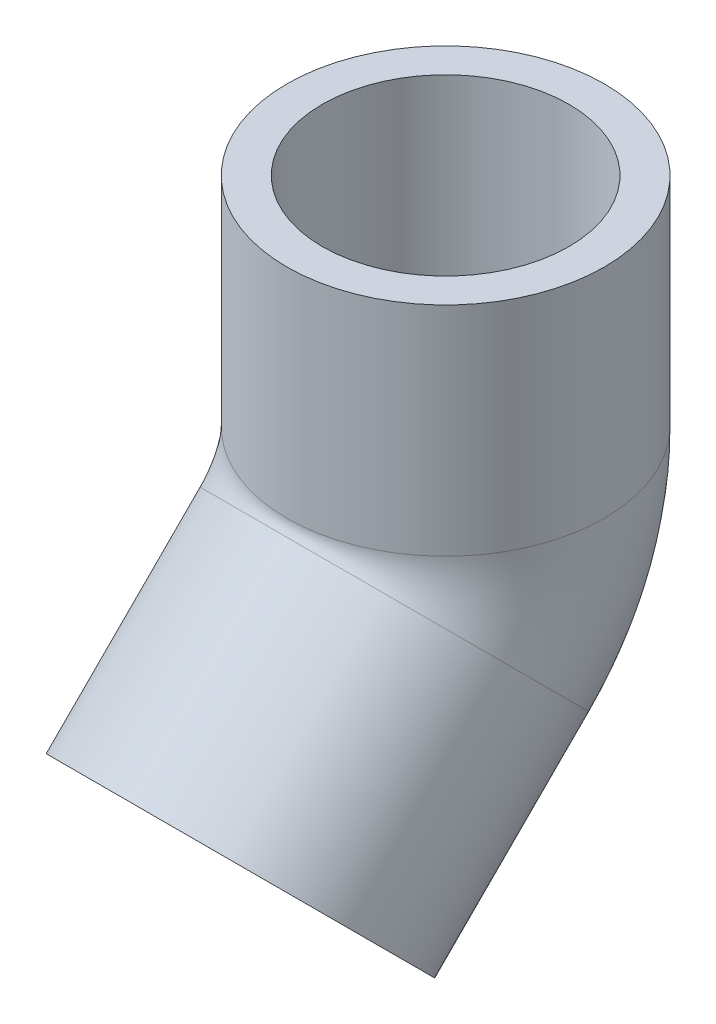
SolidWorks part; units mm, degrees
ref_plane "Front Plane" through (0, 0, 0) normal (0, 0, 1) x (1, 0, 0)
ref_plane "Top Plane" through (0, 0, 0) normal (0, 1, 0) x (1, 0, 0)
ref_plane "Right Plane" through (0, 0, 0) normal (1, 0, 0) x (0, 0, -1)
sketch "Sketch1" plane through (0, 0, 0) normal (1, 0, 0) x (0, 0, -1)
  line L0 (0, 0) -> (0, 25.4) construction
  line L1 (0, 0) -> (-17.9605, -17.9605) construction
  line L2 (-10.795, 6.35) -> (10.795, 6.35) construction
  line L3 (-13.8906, 25.4) -> (13.8906, 25.4) construction
  line L4 (7.8994, 0) -> (-7.8994, 0) construction
  line L5 (-12.1233, 3.1431) -> (3.1431, -12.1233) construction
  line L6 (-27.7827, -8.1384) -> (-8.1384, -27.7827) construction
  point P7 (0, 6.35)
  point P10 (0, 25.4)
  point P13 (0, 0)
  point P16 (-4.4901, -4.4901)
  point P19 (-17.9605, -17.9605)
  dimension "D1" = 45
  dimension "Leg Length" = 25.4
  dimension "Center to Socket" = 6.35
  dimension "Elbow OD" = 27.7812
  dimension "For Pipe OD" = 21.59
  dimension "Pipe ID" = 15.7988
  dimension "D2" = 19.05
  dimension "D3" = 6.35
sketch "Sketch2" plane through (0, 0, 0) normal (1, 0, 0) x (0, 0, -1)
  line L0 (-17.9605, -17.9605) -> (-4.4901, -4.4901)
  line L1 (0, 0) -> (-17.9605, -17.9605) construction
  line L2 (0, 25.4) -> (0, 6.35)
  line L3 (0, 0) -> (0, 25.4) construction
  line L4 (-10.795, 6.35) -> (10.795, 6.35) construction
  arc A0 (-4.4901, -4.4901) -> (0, 6.35) centre (-15.3303, 6.35) ccw
ref_plane "Plane1" through (0, 25.4, 0) normal (0, 1, 0) x (1, 0, 0)
sketch "Sketch3" plane through (0, 25.4, 0) normal (0, 1, 0) x (1, 0, 0)
  circle A0 centre (0, 0) radius 13.8906
  circle A1 centre (0, 0) radius 7.8994
  dimension "D1" = 27.7812
  dimension "D2" = 15.7988
sweep "Sweep1" add profiles "Sketch3" path "Sketch2"
sketch "Sketch4" plane through (0, 25.4, 0) normal (0, 1, 0) x (1, 0, 0)
  circle A0 centre (0, 0) radius 10.795
  dimension "D1" = 21.59
extrude "Cut-Extrude1" cut sketch "Sketch4" against normal blind 19.05
sketch "Sketch5" plane through (0, -17.9605, 17.9605) normal (0, -0.7071, 0.7071) x (1, 0, 0)
  circle A0 centre (0, 0) radius 10.795
  dimension "D1" = 21.59
extrude "Cut-Extrude2" cut sketch "Sketch5" against normal blind 19.05
sketch "Sketch6" plane through (0, 0, 0) normal (1, 0, 0) x (0, 0, -1)
  line L0 (3.1431, -12.1233) -> (-10.3273, -25.5937) construction
  line L1 (-12.1233, 3.1431) -> (-25.5937, -10.3273) construction
  line L2 (-27.7827, -8.1384) -> (-8.1384, -27.7827) construction
  line L3 (10.795, 6.35) -> (10.795, 25.4) construction
  line L4 (-10.795, 6.35) -> (-10.795, 25.4) construction
  line L5 (-13.8906, 25.4) -> (13.8906, 25.4) construction
  line L6 (-10.795, 6.35) -> (-7.8994, 6.35) construction
  line L7 (-10.795, 6.35) -> (10.795, 6.35) construction
  line L8 (10.795, 6.35) -> (7.8994, 6.35) construction
  line L9 (-12.1233, 3.1431) -> (-10.0758, 1.0956) construction
  line L10 (-12.1233, 3.1431) -> (3.1431, -12.1233) construction
  line L11 (3.1431, -12.1233) -> (1.0956, -10.0758) construction
  arc A0 (-7.8994, 6.35) -> (-10.0758, 1.0956) centre (-15.3303, 6.35) cw construction
  arc A1 (1.0956, -10.0758) -> (7.8994, 6.35) centre (-15.3303, 6.35) ccw construction
  arc A2 (-4.4901, -4.4901) -> (0, 6.35) centre (-15.3303, 6.35) ccw construction
sketch "Sketch7" plane through (0, -17.9605, 17.9605) normal (0, -0.7071, 0.7071) x (1, 0, 0)
  circle A0 centre (0, 0) radius 10.795 construction
  circle A1 centre (0, 0) radius 10.795 construction
  circle A2 centre (0, 0) radius 13.8906 construction
  circle A3 centre (0, 0) radius 13.8906 construction
  point P3 (0, -10.795)
  point P4 (10.795, 0)
  point P5 (0, 10.795)
  point P6 (-10.795, 0)
  point P9 (0, -13.8906)
  point P10 (13.8906, 0)
  point P11 (-13.8906, 0)
  point P12 (0, 13.8906)
equation "\"D1@Sketch3\"=\"Elbow OD@Sketch1\""
equation "\"D2@Sketch3\"=\"Pipe ID@Sketch1\""
equation "\"D1@Sketch4\"=\"For Pipe OD@Sketch1\""
equation "\"D1@Cut-Extrude1\"=\"D2@Sketch1\""
equation "\"D1@Sketch5\"=\"For Pipe OD@Sketch1\""
equation "\"D1@Cut-Extrude2\"=\"D2@Sketch1\""
equation "\"D3@Sketch1\"=\"Center to Socket@Sketch1\""
